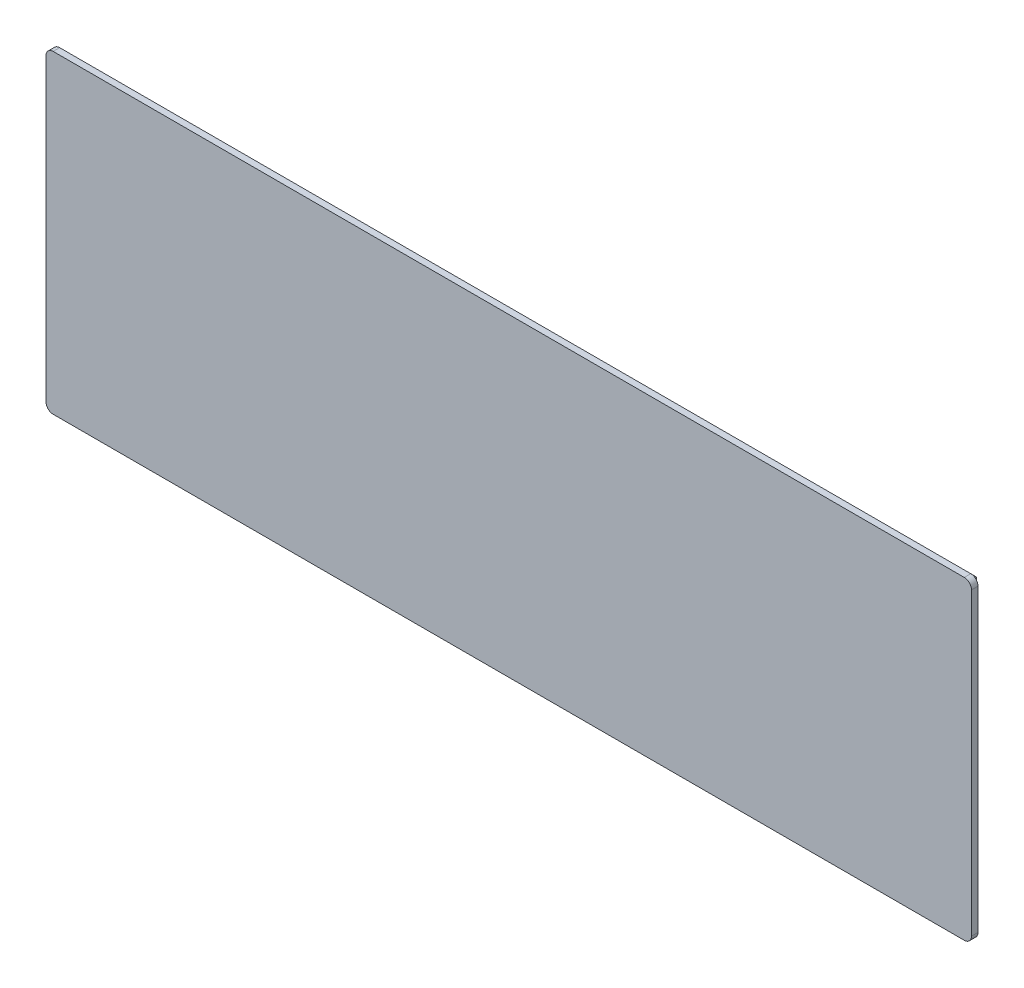
SolidWorks part; units mm, degrees
ref_plane "Front Plane" through (0, 0, 0) normal (0, 0, 1) x (1, 0, 0)
ref_plane "Top Plane" through (0, 0, 0) normal (0, 1, 0) x (1, 0, 0)
ref_plane "Right Plane" through (0, 0, 0) normal (1, 0, 0) x (0, 0, -1)
sketch "Sketch1" plane through (0, 0, 0) normal (0, 0, 1) x (1, 0, 0)
  line L1 (-158, -54.5) -> (158, -54.5)
  line L2 (-160.5, -52) -> (-160.5, 52)
  line L3 (-158, 54.5) -> (158, 54.5)
  line L4 (160.5, -52) -> (160.5, 52)
  line L5 (-160.5, -54.5) -> (160.5, 54.5) construction
  line L6 (-160.5, 54.5) -> (160.5, -54.5) construction
  arc A0 (158, -54.5) -> (160.5, -52) centre (158, -52) ccw
  arc A1 (158, 54.5) -> (160.5, 52) centre (158, 52) cw
  arc A2 (-160.5, 52) -> (-158, 54.5) centre (-158, 52) cw
  arc A3 (-158, -54.5) -> (-160.5, -52) centre (-158, -52) cw
  point P0 (0, 0)
  dimension "D3" = 2.5
  dimension "D1" = 109
  dimension "D2" = 321
extrude "DIGITIZER" add sketch "Sketch1" along normal blind 2.25
sketch "Sketch2" plane through (0, 0, 0) normal (0, 0, -1) x (-1, 0, 0)
  line L1 (-157.5, 52) -> (157.5, 52)
  line L2 (-157.5, 52) -> (-157.5, -52)
  line L3 (-157.5, -52) -> (157.5, -52)
  line L4 (157.5, 52) -> (157.5, -52)
  point P4 (0, 52)
  point P6 (-157.5, 0)
  dimension "D1" = 104
  dimension "D2" = 315
extrude "DISPLAY INCLUDING ADHESIVE MARGIN OF .5MM" add sketch "Sketch2" along normal blind 2.5
sketch "Sketch3" plane through (0, 0, 0) normal (0, 0, -1) x (-1, 0, 0)
  line L0 (-157.5, -52) -> (157.5, -52) construction
  line L1 (-35, -52) -> (35, -52)
  line L2 (-35, -52) -> (-35, -54.5)
  line L3 (-35, -54.5) -> (35, -54.5)
  line L4 (35, -52) -> (35, -54.5)
  line L5 (158, -54.5) -> (-158, -54.5) construction
  point P8 (0, -52)
  dimension "D1" = 70
extrude "DIGITIZER CABLE" add sketch "Sketch3" along normal up to surface (2.5 mm away) up to face at (0, 0, -2.5)
